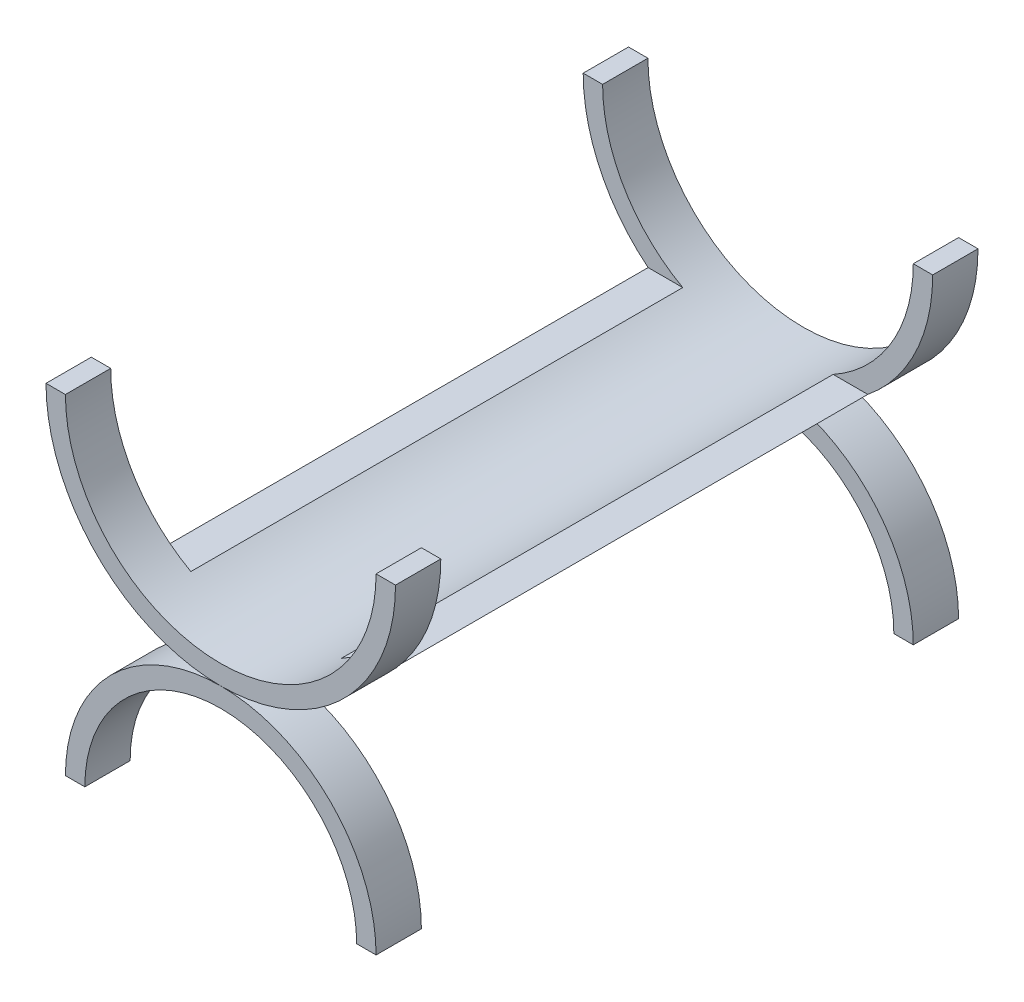
SolidWorks part; units mm, degrees
ref_plane "Front Plane" through (0, 0, 0) normal (0, 0, 1) x (1, 0, 0)
ref_plane "Top Plane" through (0, 0, 0) normal (0, 1, 0) x (1, 0, 0)
ref_plane "Right Plane" through (0, 0, 0) normal (1, 0, 0) x (0, 0, -1)
sketch "Sketch1" plane through (0, 0, 0) normal (0, 0, 1) x (1, 0, 0)
  line L0 (-304.8, 0) -> (304.8, 0) construction
  line L1 (-342.9, 0) -> (-304.8, 0)
  line L2 (304.8, 0) -> (342.9, 0)
  arc A0 (-304.8, 0) -> (304.8, 0) centre (0, 0) ccw
  arc A1 (-342.9, 0) -> (342.9, 0) centre (0, 0) ccw
  dimension "D1" = 609.6
  dimension "D2" = 38.1
extrude "Boss-Extrude1" add sketch "Sketch1" against normal mid plane 1143
sketch "Sketch2" plane through (0, 0, 0) normal (1, 0, 0) x (0, 0, -1)
  line L0 (571.5, 0) -> (-571.5, 0) construction
  line L1 (-482.6, 0) -> (482.6, 0)
  line L2 (-482.6, 0) -> (-482.6, -266.7)
  line L3 (-482.6, -266.7) -> (482.6, -266.7)
  line L4 (482.6, 0) -> (482.6, -266.7)
  line L5 (-571.5, 0) -> (-571.5, -342.9) construction
  line L6 (571.5, -342.9) -> (571.5, 0) construction
  line L7 (-571.5, -342.9) -> (571.5, -342.9) construction
  dimension "D1" = 88.9
  dimension "D2" = 88.9
  dimension "D3" = 76.2
extrude "Cut-Extrude1" cut sketch "Sketch2" against normal through all both and the other way through all
sketch "Sketch3" plane through (0, 0, 571.5) normal (0, 0, 1) x (1, 0, 0)
  line L0 (-304.8, -647.7) -> (-266.7, -647.7)
  line L1 (266.7, -647.7) -> (304.8, -647.7)
  arc A0 (-304.8, -647.7) -> (304.8, -647.7) centre (0, -647.7) cw
  arc A1 (-342.9, 0) -> (342.9, 0) centre (0, 0) ccw construction
  arc A2 (-266.7, -647.7) -> (266.7, -647.7) centre (0, -647.7) cw
  dimension "D1" = 304.8
  dimension "D2" = 38.1
extrude "Boss-Extrude2" add sketch "Sketch3" against normal blind 88.9 separate body
mirror "Mirror4" about plane through (0, 0, 0) normal (0, 0, 1) of bodies 103
